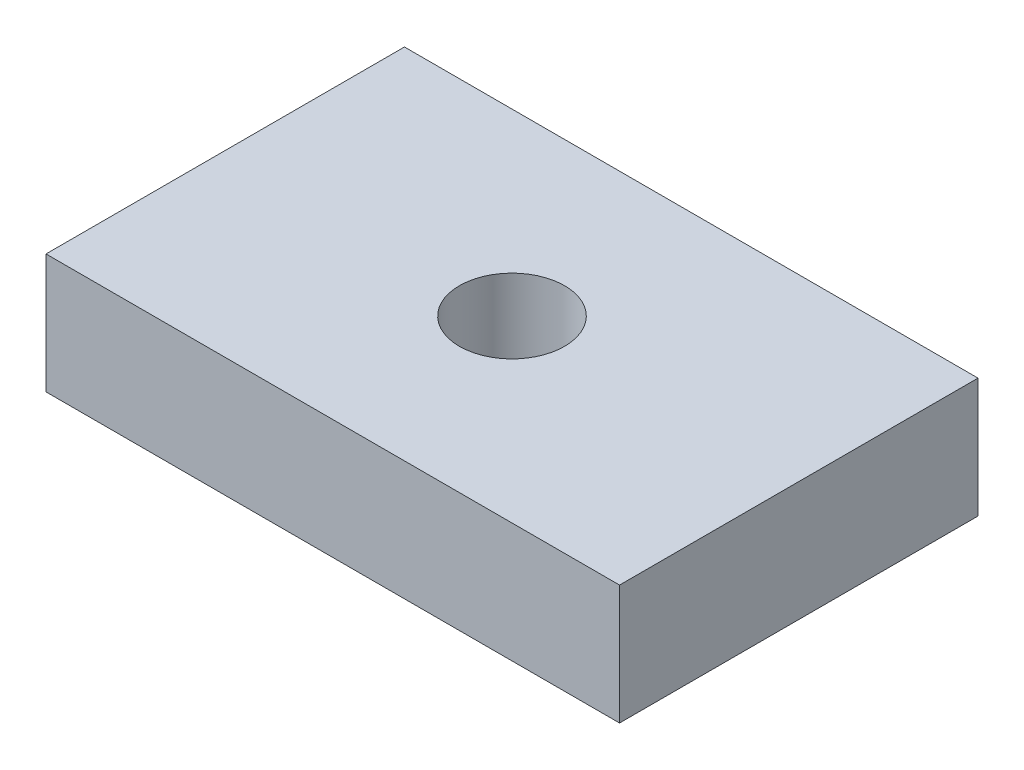
SolidWorks part; units mm, degrees
ref_plane "Front Plane" through (0, 0, 0) normal (0, 0, 1) x (1, 0, 0)
ref_plane "Top Plane" through (0, 0, 0) normal (0, 1, 0) x (1, 0, 0)
ref_plane "Right Plane" through (0, 0, 0) normal (1, 0, 0) x (0, 0, -1)
sketch "Sketch1" plane through (0, 0, 0) normal (0, 1, 0) x (1, 0, 0)
  line L1 (12, -7.5) -> (-12, -7.5)
  line L2 (12, -7.5) -> (12, 7.5)
  line L3 (12, 7.5) -> (-12, 7.5)
  line L4 (-12, -7.5) -> (-12, 7.5)
  line L5 (12, -7.5) -> (-12, 7.5) construction
  line L6 (12, 7.5) -> (-12, -7.5) construction
  circle A0 centre (0, 0) radius 2.2
  dimension "D1" = 24
  dimension "D3" = 4.4
  dimension "D2" = 15
extrude "Boss-Extrude1" add sketch "Sketch1" along normal blind 5
